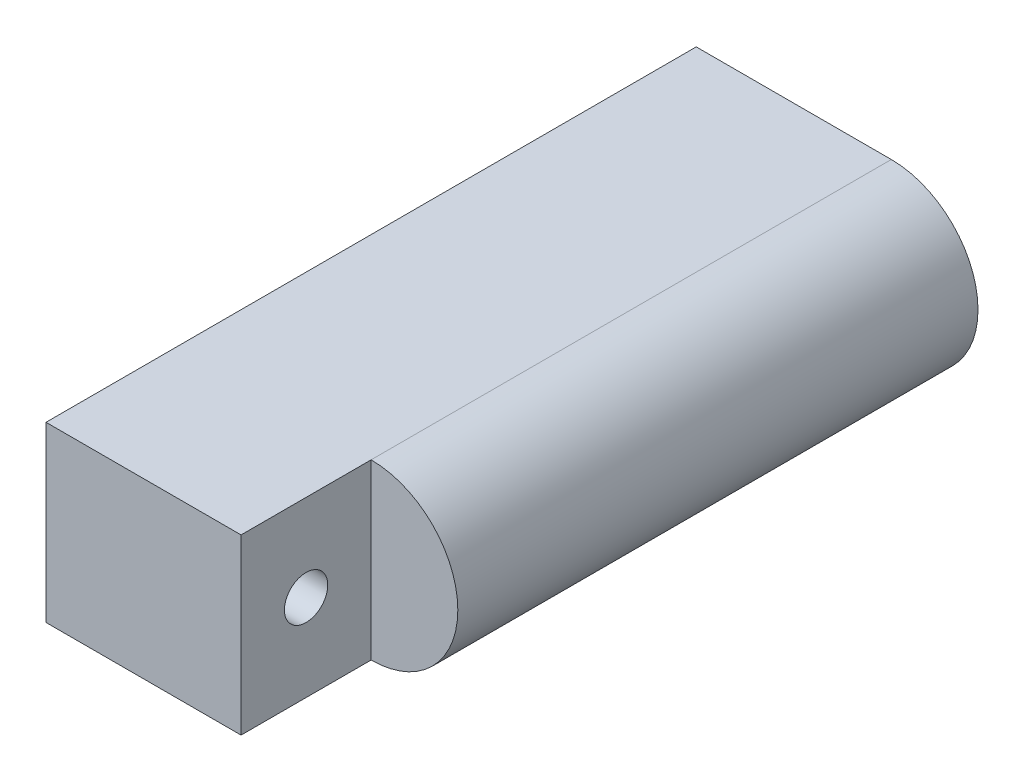
SolidWorks part; units mm, degrees
ref_plane "Alzado" through (0, 0, 0) normal (0, 0, 1) x (1, 0, 0)
ref_plane "Planta" through (0, 0, 0) normal (0, 1, 0) x (1, 0, 0)
ref_plane "Vista lateral" through (0, 0, 0) normal (1, 0, 0) x (0, 0, -1)
sketch "Croquis1" plane through (0, 0, 0) normal (0, 0, 1) x (1, 0, 0)
  line L1 (-22.5, -20) -> (22.5, -20)
  line L2 (-22.5, -20) -> (-22.5, 20)
  line L3 (-22.5, 20) -> (22.5, 20)
  line L5 (-22.5, -20) -> (22.5, 20) construction
  line L6 (-22.5, 20) -> (22.5, -20) construction
  arc A0 (22.5, -20) -> (22.5, 20) centre (22.5, 0) ccw
  point P0 (0, 0)
  dimension "D1" = 45
  dimension "D4" = 20
  dimension "D2" = 40
extrude "Saliente-Extruir1" add sketch "Croquis1" along normal blind 150
sketch "Croquis4" plane through (0, 0, 150) normal (0, 0, 1) x (1, 0, 0)
  line L1 (22.5, -20) -> (42.5, -20)
  line L2 (22.5, -20) -> (22.5, 20)
  line L3 (22.5, 20) -> (42.5, 20)
  line L4 (42.5, -20) -> (42.5, 20)
  point P4 (0, 0)
  point P5 (0, 0)
  point P6 (0, 0)
  point P10 (0, 0)
  point P11 (0, 0)
  dimension "D1" = 20
extrude "Cortar-Extruir1" cut sketch "Croquis4" against normal blind 30
sketch "Croquis5" plane through (-22.5, 0, 0) normal (-1, 0, 0) x (0, 0, 1)
  line L0 (150, 20) -> (150, -20) construction
  circle A0 centre (135, 0) radius 5
  point P4 (150, 0)
  dimension "D1" = 10
  dimension "D2" = 15
extrude "Cortar-Extruir2" cut sketch "Croquis5" against normal blind 52
